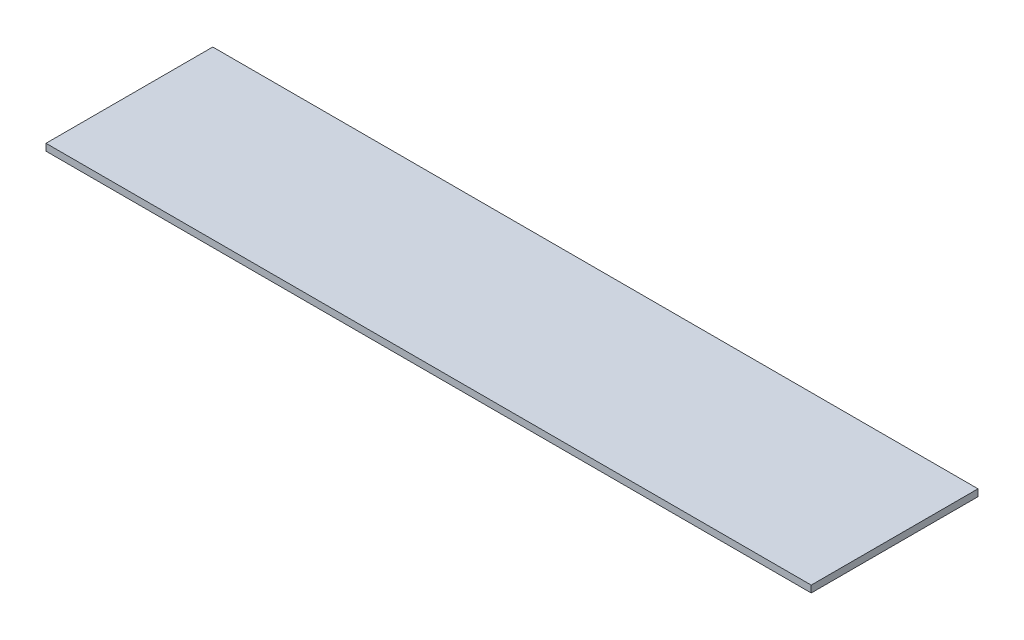
SolidWorks part; units mm, degrees
material "Mahogany"
ref_plane "Front Plane" through (0, 0, 0) normal (0, 0, 1) x (1, 0, 0)
ref_plane "Top Plane" through (0, 0, 0) normal (0, 1, 0) x (1, 0, 0)
ref_plane "Right Plane" through (0, 0, 0) normal (1, 0, 0) x (0, 0, -1)
sketch "Sketch1" plane through (0, 0, 0) normal (0, 1, 0) x (1, 0, 0)
  line L1 (-38.6164, 9.5902) -> (741.3836, 9.5902)
  line L2 (-38.6164, 9.5902) -> (-38.6164, -160.4098)
  line L3 (-38.6164, -160.4098) -> (741.3836, -160.4098)
  line L4 (741.3836, 9.5902) -> (741.3836, -160.4098)
  dimension "D1" = 780
  dimension "D2" = 170
extrude "Boss-Extrude1" add sketch "Sketch1" along normal blind 7
